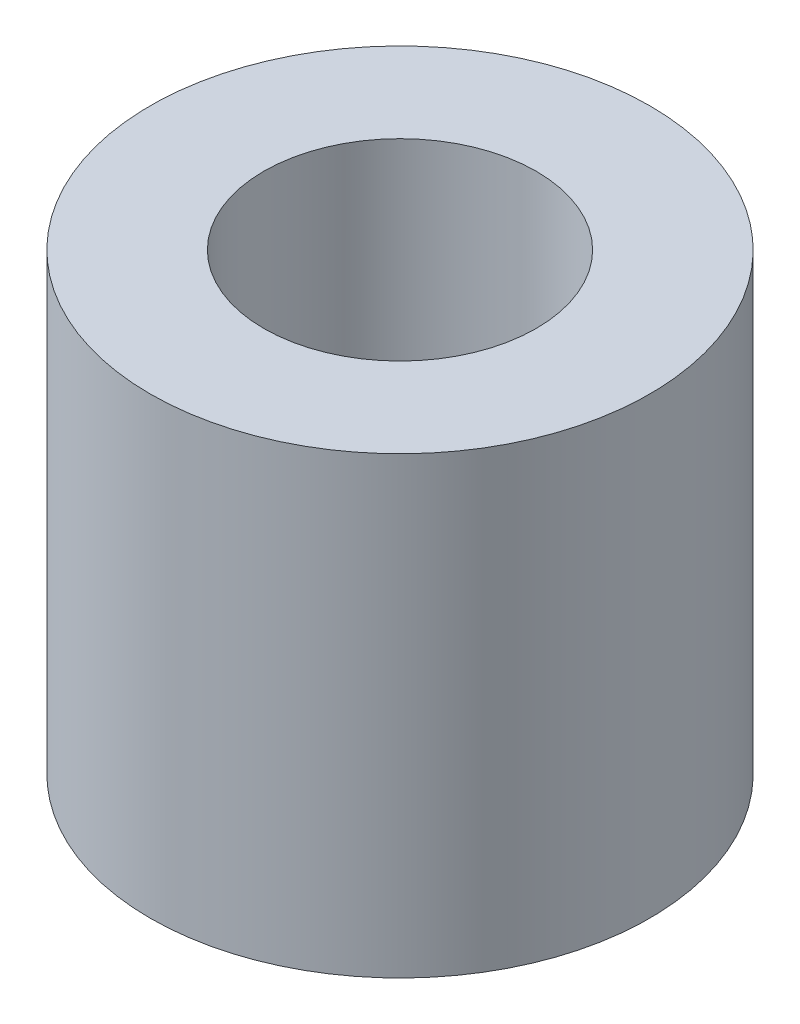
SolidWorks part; units mm, degrees
ref_plane "Front Plane" through (0, 0, 0) normal (0, 0, 1) x (1, 0, 0)
ref_plane "Top Plane" through (0, 0, 0) normal (0, 1, 0) x (1, 0, 0)
ref_plane "Right Plane" through (0, 0, 0) normal (1, 0, 0) x (0, 0, -1)
other "Configuration Table"
sketch "Sketch1" plane through (0, 0, 0) normal (0, 1, 0) x (1, 0, 0)
  circle A0 centre (0, 0) radius 2.75
extrude "Standoff_body" add sketch "Sketch1" along normal blind 5
sketch "Sketch2" plane through (0, 0, 0) normal (0, 1, 0) x (1, 0, 0)
  circle A0 centre (0, 0) radius 1.5
extrude "M3_bore" cut sketch "Sketch2" against normal through all and the other way through all
